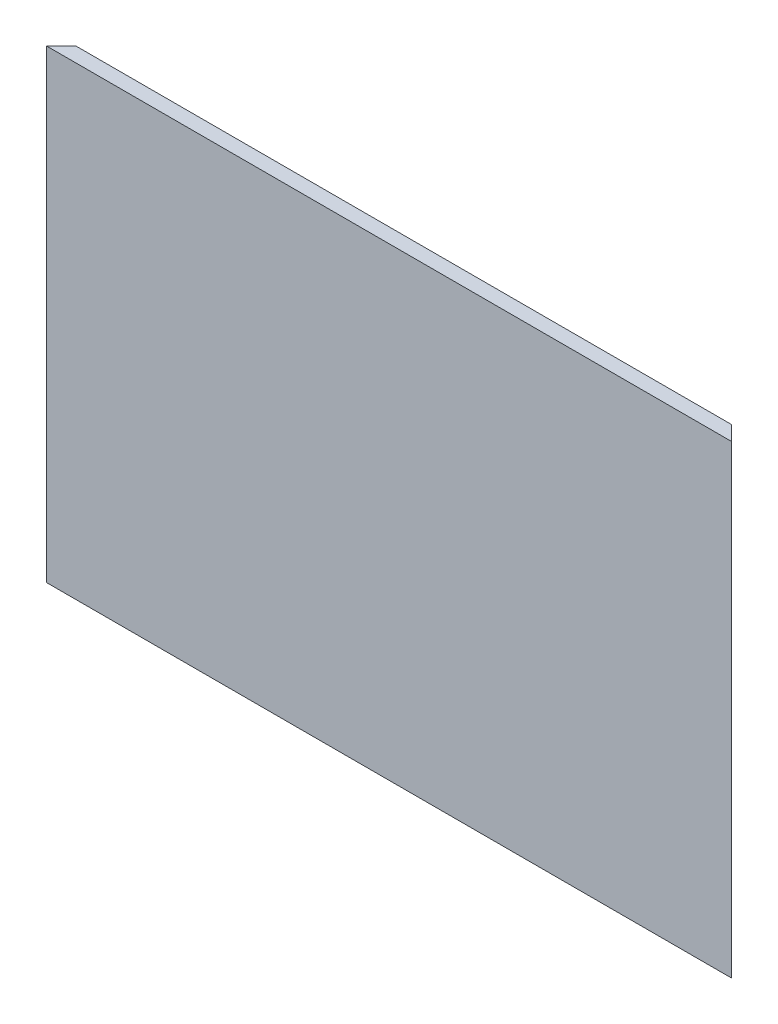
SolidWorks part; units mm, degrees
ref_plane "Front Plane" through (0, 0, 0) normal (0, 0, 1) x (1, 0, 0)
ref_plane "Top Plane" through (0, 0, 0) normal (0, 1, 0) x (1, 0, 0)
ref_plane "Right Plane" through (0, 0, 0) normal (1, 0, 0) x (0, 0, -1)
sketch "Sketch1" plane through (0, 0, 0) normal (0, 1, 0) x (1, 0, 0)
  line L1 (70, -1.5) -> (-70, -1.5)
  line L2 (70, -1.5) -> (70, 1.5)
  line L3 (70, 1.5) -> (-70, 1.5)
  line L4 (-70, -1.5) -> (-70, 1.5)
  line L5 (70, -1.5) -> (-70, 1.5) construction
  line L6 (70, 1.5) -> (-70, -1.5) construction
  point P0 (0, 0)
  dimension "D1" = 140
  dimension "D2" = 3
extrude "Boss-Extrude1" add sketch "Sketch1" along normal blind 95
sketch "Sketch2" plane through (0, 95, 0) normal (0, 1, 0) x (1, 0, 0)
  line L0 (70, -1.5) -> (70, 1.5)
  line L1 (70, 1.5) -> (67, 1.5)
  line L2 (70, 1.5) -> (-70, 1.5) construction
  line L3 (67, 1.5) -> (70, -1.5)
  line L4 (-70, -1.5) -> (-70, 1.5)
  line L5 (-70, 1.5) -> (-67, 1.5)
  line L6 (-67, 1.5) -> (-70, -1.5)
  dimension "D1" = 45
  dimension "D2" = 45
extrude "Cut-Extrude1" cut sketch "Sketch2" against normal blind 95
